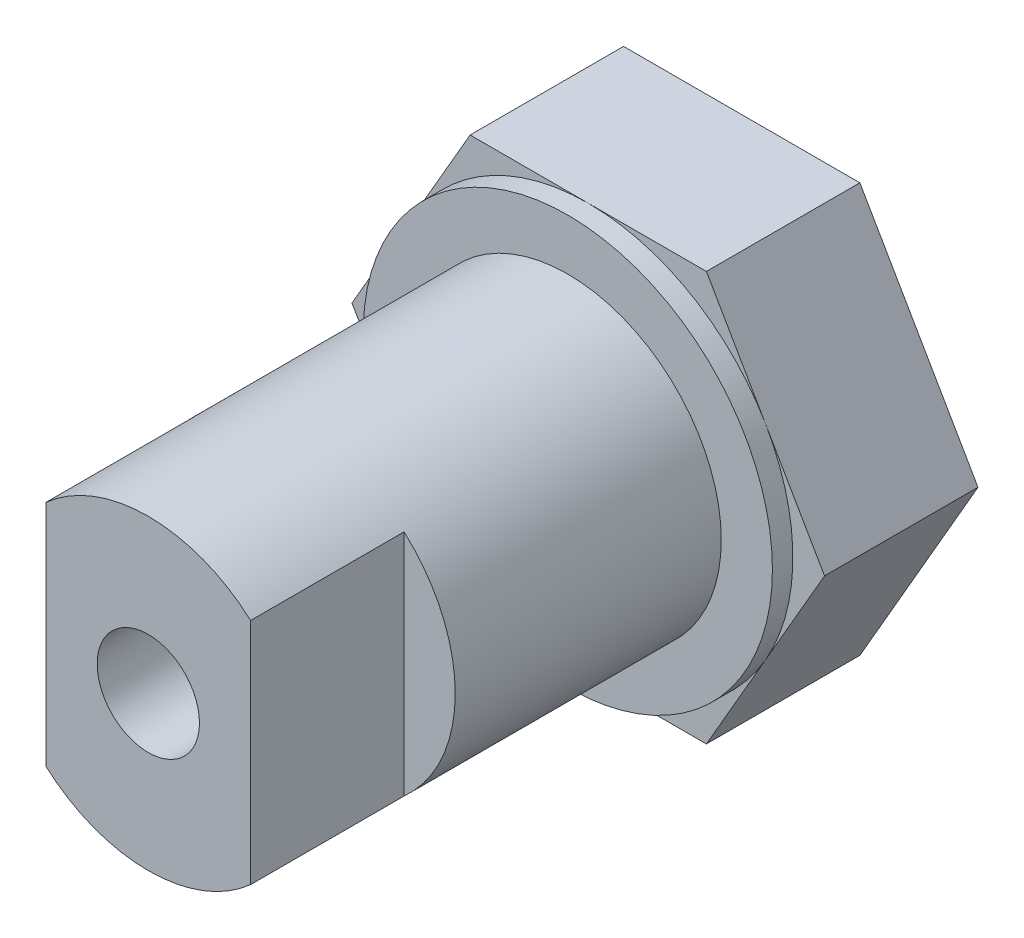
SolidWorks part; units mm, degrees
ref_plane "Front Plane" through (0, 0, 0) normal (0, 0, 1) x (1, 0, 0)
ref_plane "Top Plane" through (0, 0, 0) normal (0, 1, 0) x (1, 0, 0)
ref_plane "Right Plane" through (0, 0, 0) normal (1, 0, 0) x (0, 0, -1)
sketch "Sketch1" plane through (0, 0, 0) normal (0, 0, 1) x (1, 0, 0)
  line L0 (0, 0) -> (20, 0)
  line L2 (23.094, 0) -> (11.547, 20)
  line L3 (11.547, 20) -> (-11.547, 20)
  line L4 (-11.547, 20) -> (-23.094, 0)
  line L5 (-23.094, 0) -> (-11.547, -20)
  line L6 (-11.547, -20) -> (11.547, -20)
  line L7 (11.547, -20) -> (23.094, 0)
  circle A0 centre (0, 0) radius 5
  circle A1 centre (0, 0) radius 15
  circle A2 centre (0, 0) radius 20
  circle A3 centre (0, 0) radius 20
  circle A4 centre (0, 0) radius 20
  circle A5 centre (0, 0) radius 20
  circle A6 centre (0, 0) radius 20
  circle A7 centre (0, 0) radius 20
  circle A8 centre (0, 0) radius 20 construction
  point P26 (0, 0)
  dimension "D1" = 10
  dimension "D2" = 30
  dimension "D3" = 40
  dimension "D4" = 40
  dimension "D6" = 6
extrude "Boss-Extrude5" add sketch "Sketch1" along normal blind 15 contours L3 L4 L5 L6 L7 L2
sketch "Sketch4" plane through (0, 0, 15) normal (0, 0, 1) x (1, 0, 0)
  circle A0 centre (0, 0) radius 20
  dimension "D1" = 40
extrude "Boss-Extrude6" add sketch "Sketch4" along normal blind 2
sketch "Sketch5" plane through (0, 0, 17) normal (0, 0, 1) x (1, 0, 0)
  circle A0 centre (0, 0) radius 15
  dimension "D1" = 30
extrude "Boss-Extrude7" add sketch "Sketch5" along normal blind 41
sketch "Sketch6" plane through (0, 0, 58) normal (0, 0, 1) x (1, 0, 0)
  circle A0 centre (0, 0) radius 5
  dimension "D1" = 10
extrude "Cut-Extrude2" cut sketch "Sketch6" against normal blind 100 contours A0
sketch "Sketch9" plane through (0, 0, 58) normal (0, 0, 1) x (1, 0, 0)
  line L0 (-5, 0) -> (-10, 0)
  line L1 (-10, 11.1803) -> (-10, -11.1803)
  line L2 (-5, 0) -> (5, 0)
  line L3 (5, 0) -> (10, 0)
  line L4 (10, 0) -> (10, 11.1803)
  line L5 (10, 11.1803) -> (10, -11.1803)
  line L6 (-10, 11.1803) -> (-21.041, 11.1803)
  line L7 (-10, -11.1803) -> (-21.041, -11.1803)
  line L8 (-21.041, -11.1803) -> (-21.041, 11.1803)
  line L9 (10, -11.1803) -> (18.1, -11.1803)
  line L10 (18.1, -11.1803) -> (18.1, 11.1803)
  line L11 (18.1, 11.1803) -> (10, 11.1803)
  circle A0 centre (0, 0) radius 5 construction
  circle A1 centre (0, 0) radius 15 construction
  circle M4 centre (0, 0) radius 15
  dimension "D1" = 5
  dimension "D2" = 5
extrude "Cut-Extrude3" cut sketch "Sketch9" against normal blind 15 contours L1 M4 | L4 L5 M4
